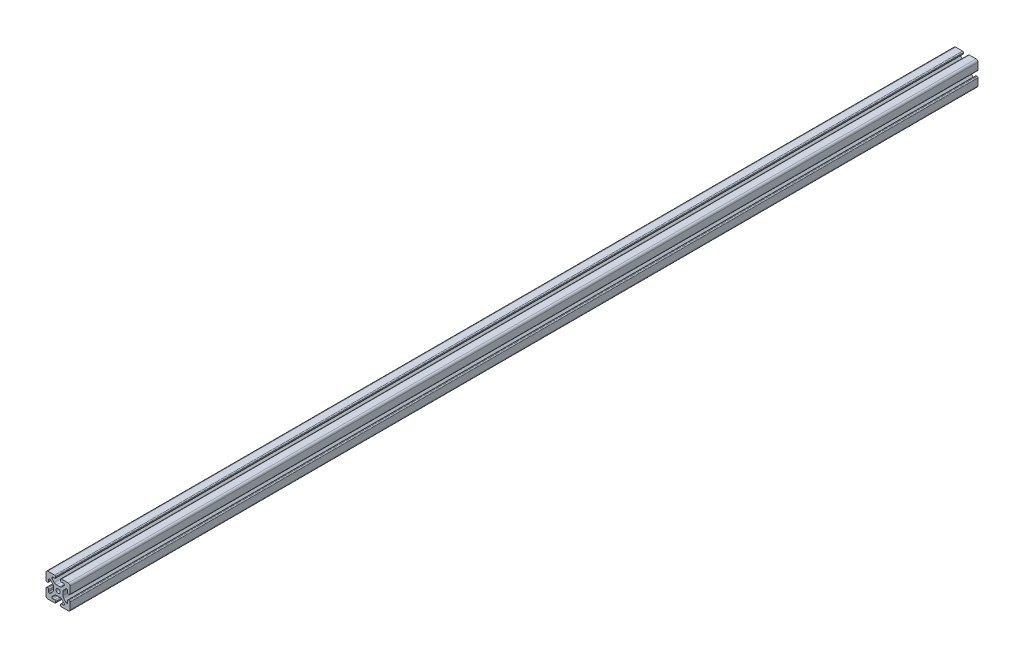
SolidWorks part; units mm, degrees
material "6061 Alloy"
ref_plane "Front Plane" through (0, 0, 0) normal (0, 0, 1) x (1, 0, 0)
ref_plane "Top Plane" through (0, 0, 0) normal (0, 1, 0) x (1, 0, 0)
ref_plane "Right Plane" through (0, 0, 0) normal (1, 0, 0) x (0, 0, -1)
sketch "Sketch1" plane through (0, 0, 0) normal (0, 0, 1) x (1, 0, 0)
  line L0 (0, 19.7407) -> (0, -19.7407) construction
  line L1 (19.0335, 0) -> (-20.7246, 0) construction
  line L2 (-8.715, -15.5246) -> (-5.63, -15.5246)
  line L3 (-10.285, -13.9546) -> (-10.285, -13.4925)
  line L4 (-6.2171, -9.1098) -> (-10.0624, -12.9551)
  line L5 (2.7773, -7.685) -> (-2.7773, -7.685)
  line L6 (10.0624, -12.9551) -> (6.2171, -9.1098)
  line L7 (10.285, -13.9546) -> (10.285, -13.4925)
  line L8 (5.63, -15.5246) -> (8.715, -15.5246)
  line L9 (4.06, -18.43) -> (4.06, -17.0946)
  line L10 (-4.06, -18.43) -> (-4.06, -17.0946)
  line L11 (15.68, -8.7154) -> (15.68, -5.63)
  line L12 (-14.11, -10.2854) -> (-13.8169, -10.2854)
  line L13 (20, -16.83) -> (20, -5.63)
  line L14 (20, 5.63) -> (20, 13.0011)
  line L15 (-16.83, 20) -> (-5.63, 20)
  line L16 (5.63, 20) -> (12.9796, 20)
  line L18 (-8.715, 15.5246) -> (-5.63, 15.5246)
  line L19 (-20, -17.0184) -> (-20, -5.7579)
  line L20 (-20, 5.573) -> (-20, 13.0045)
  line L21 (-15.68, -8.7154) -> (-15.68, -5.7579)
  line L23 (-16.6746, -20) -> (-5.63, -20)
  line L24 (5.63, -20) -> (13, -20)
  line L53 (14.11, -10.2854) -> (13.6201, -10.2854)
  line L54 (13.1637, -9.947) -> (9.0762, -5.8595)
  line L55 (7.685, -2.5008) -> (7.685, 2.5008)
  line L56 (9.0762, 5.8595) -> (13.2795, 10.0628)
  line L57 (13.8169, 10.2854) -> (14.11, 10.2854)
  line L58 (15.68, 8.7154) -> (15.68, 5.63)
  line L59 (17.25, 4.06) -> (18.43, 4.06)
  line L61 (20, 13.0011) -> (20, 16.83)
  line L62 (16.83, 20) -> (12.9796, 20)
  line L64 (4.06, 18.43) -> (4.06, 17.0946)
  line L65 (5.63, 15.5246) -> (8.715, 15.5246)
  line L66 (10.285, 13.9546) -> (10.285, 13.4925)
  line L67 (10.0624, 12.9551) -> (6.2171, 9.1098)
  line L68 (2.7773, 7.685) -> (-2.7773, 7.685)
  line L69 (-6.2171, 9.1098) -> (-10.0624, 12.9551)
  line L70 (-10.285, 13.4925) -> (-10.285, 13.9546)
  line L72 (-4.06, 17.0946) -> (-4.06, 18.43)
  line L75 (-20, 16.83) -> (-20, 13.0045)
  line L77 (-18.43, 4.003) -> (-17.25, 4.003)
  line L78 (-15.68, 5.573) -> (-15.68, 8.4757)
  line L79 (-14.0552, 10.0447) -> (-13.7199, 10.033)
  line L80 (-13.0405, 9.8238) -> (-9.0762, 5.8595)
  line L81 (-7.685, 2.5008) -> (-7.685, -2.5008)
  line L82 (-9.0762, -5.8595) -> (-13.2795, -10.0628)
  line L85 (-17.25, -4.1204) -> (-18.43, -4.1204)
  line L100 (13, -20) -> (16.83, -20)
  line L103 (18.43, -4.06) -> (17.25, -4.06)
  arc A0 (-5.63, -15.5246) -> (-4.06, -17.0946) centre (-5.63, -17.0946) cw
  arc A1 (-8.715, -15.5246) -> (-10.285, -13.9546) centre (-8.715, -13.9546) cw
  arc A2 (-10.285, -13.4925) -> (-10.0624, -12.9551) centre (-9.525, -13.4925) cw
  arc A3 (-6.2171, -9.1098) -> (-2.7773, -7.685) centre (-2.7773, -12.5496) cw
  arc A4 (2.7773, -7.685) -> (6.2171, -9.1098) centre (2.7773, -12.5496) cw
  arc A5 (10.0624, -12.9551) -> (10.285, -13.4925) centre (9.525, -13.4925) cw
  arc A6 (10.285, -13.9546) -> (8.715, -15.5246) centre (8.715, -13.9546) cw
  arc A7 (4.06, -17.0946) -> (5.63, -15.5246) centre (5.63, -17.0946) cw
  arc A8 (5.63, -20) -> (4.06, -18.43) centre (5.63, -18.43) cw
  arc A9 (-4.06, -18.43) -> (-5.63, -20) centre (-5.63, -18.43) cw
  circle A45 centre (0, 0) radius 3.4
  arc A46 (17.25, -4.06) -> (15.68, -5.63) centre (17.25, -5.63) ccw
  arc A47 (14.11, -10.2854) -> (15.68, -8.7154) centre (14.11, -8.7154) ccw
  arc A48 (13.1637, -9.947) -> (13.6201, -10.2854) centre (13.8117, -9.55) ccw
  arc A49 (7.685, -2.5008) -> (9.0762, -5.8595) centre (12.435, -2.5008) ccw
  arc A50 (9.0762, 5.8595) -> (7.685, 2.5008) centre (12.435, 2.5008) ccw
  arc A51 (13.8169, 10.2854) -> (13.2795, 10.0628) centre (13.8169, 9.5254) ccw
  arc A52 (15.68, 8.7154) -> (14.11, 10.2854) centre (14.11, 8.7154) ccw
  arc A53 (15.68, 5.63) -> (17.25, 4.06) centre (17.25, 5.63) ccw
  arc A54 (18.43, 4.06) -> (20, 5.63) centre (18.43, 5.63) ccw
  arc A55 (20, 16.83) -> (16.83, 20) centre (16.83, 16.83) ccw
  arc A56 (5.63, 20) -> (4.06, 18.43) centre (5.63, 18.43) ccw
  arc A57 (4.06, 17.0946) -> (5.63, 15.5246) centre (5.63, 17.0946) ccw
  arc A58 (10.285, 13.9546) -> (8.715, 15.5246) centre (8.715, 13.9546) ccw
  arc A59 (10.0624, 12.9551) -> (10.285, 13.4925) centre (9.525, 13.4925) ccw
  arc A60 (2.7773, 7.685) -> (6.2171, 9.1098) centre (2.7773, 12.5496) ccw
  arc A61 (-6.2171, 9.1098) -> (-2.7773, 7.685) centre (-2.7773, 12.5496) ccw
  arc A62 (-10.285, 13.4925) -> (-10.0624, 12.9551) centre (-9.525, 13.4925) ccw
  arc A63 (-8.715, 15.5246) -> (-10.285, 13.9546) centre (-8.715, 13.9546) ccw
  arc A64 (-5.63, 15.5246) -> (-4.06, 17.0946) centre (-5.63, 17.0946) ccw
  arc A65 (-4.06, 18.43) -> (-5.63, 20) centre (-5.63, 18.43) ccw
  arc A66 (-16.83, 20) -> (-20, 16.83) centre (-16.83, 16.83) ccw
  arc A67 (-20, 5.573) -> (-18.43, 4.003) centre (-18.43, 5.573) ccw
  arc A68 (-17.25, 4.003) -> (-15.68, 5.573) centre (-17.25, 5.573) ccw
  arc A69 (-14.0552, 10.0447) -> (-15.68, 8.4757) centre (-14.11, 8.4757) ccw
  arc A70 (-13.0405, 9.8238) -> (-13.7199, 10.033) centre (-13.5779, 9.2864) ccw
  arc A71 (-7.685, 2.5008) -> (-9.0762, 5.8595) centre (-12.435, 2.5008) ccw
  arc A72 (-9.0762, -5.8595) -> (-7.685, -2.5008) centre (-12.435, -2.5008) ccw
  arc A73 (-13.8169, -10.2854) -> (-13.2795, -10.0628) centre (-13.8169, -9.5254) ccw
  arc A74 (-15.68, -8.7154) -> (-14.11, -10.2854) centre (-14.11, -8.7154) ccw
  arc A75 (-15.68, -5.7579) -> (-17.25, -4.1204) centre (-17.2485, -5.6904) ccw
  arc A76 (-18.43, -4.1204) -> (-20, -5.7579) centre (-18.4315, -5.6904) ccw
  arc A77 (-20, -17.0184) -> (-16.6746, -20) centre (-16.8354, -16.8341) ccw
  arc A88 (16.83, -20) -> (20, -16.83) centre (16.83, -16.83) ccw
  arc A89 (20, -5.63) -> (18.43, -4.06) centre (18.43, -5.63) ccw
  dimension "D2" = 6.8
  dimension "D7" = 20.57
  dimension "D1" = 40
  dimension "D3" = 4.32
  dimension "D4" = 15.37
  dimension "D5" = 20
  dimension "D6" = 4.32
  dimension "D9" = 15.37
extrude "Extrude1" add sketch "Sketch1" against normal blind 1500
